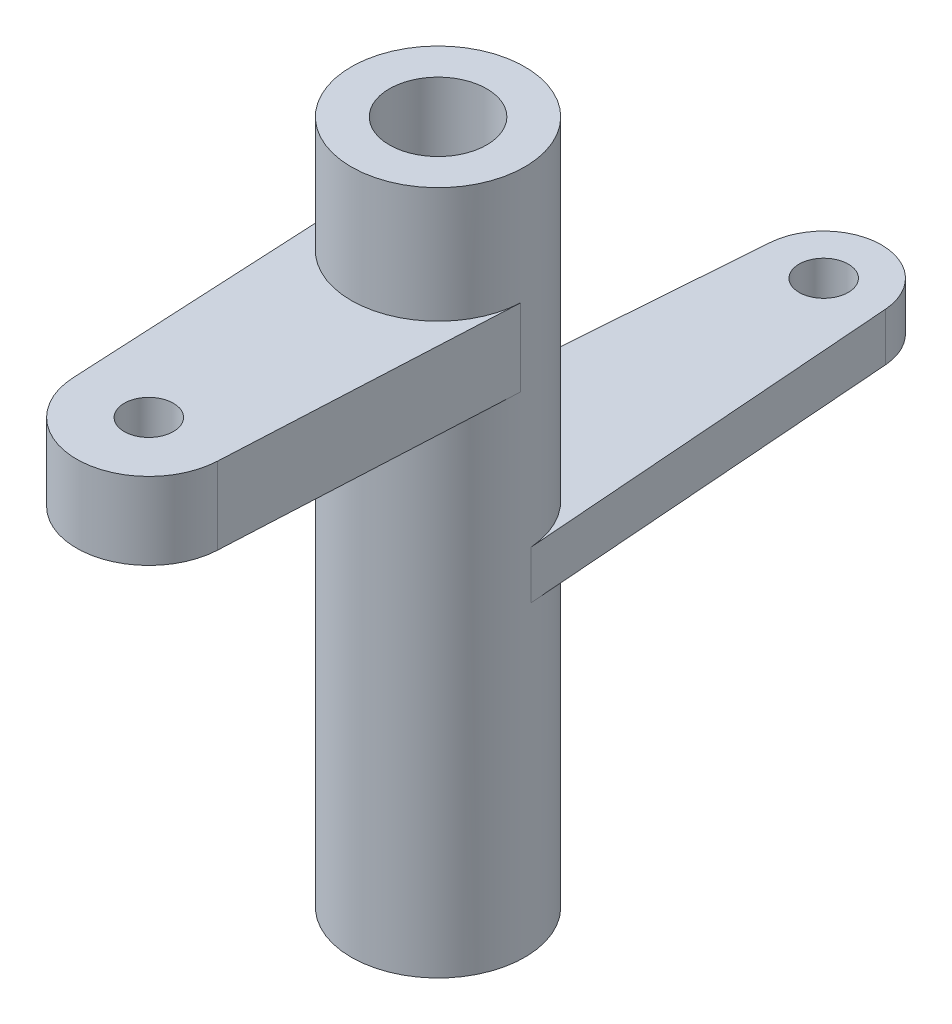
SolidWorks part; units mm, degrees
ref_plane "前视基准面" through (0, 0, 0) normal (0, 0, 1) x (1, 0, 0)
ref_plane "上视基准面" through (0, 0, 0) normal (0, 1, 0) x (1, 0, 0)
ref_plane "右视基准面" through (0, 0, 0) normal (1, 0, 0) x (0, 0, -1)
sketch "草图1" plane through (0, 0, 0) normal (0, 1, 0) x (1, 0, 0)
  circle A0 centre (0, 0) radius 5.05
  circle A1 centre (0, 0) radius 9
  dimension "D1" = 10.1
  dimension "D2" = 18
extrude "凸台-拉伸1" add sketch "草图1" along normal blind 71
ref_plane "基准面1" through (0, 34, 0) normal (0, 1, 0) x (1, 0, 0)
sketch "草图2" plane through (0, 34, 0) normal (0, 1, 0) x (1, 0, 0)
  line L0 (0, 0) -> (0, 40) construction
  line L1 (-5.9831, 40.45) -> (-8.9747, 0.675)
  line L2 (5.9831, 40.45) -> (8.9747, 0.675)
  circle A0 centre (0, 40) radius 6
  circle A1 centre (0, 0) radius 9 construction
  circle A2 centre (0, 0) radius 9
  circle A3 centre (0, 40) radius 2.55
  dimension "D2" = 12
  dimension "D3" = 18
  dimension "D4" = 5.1
  dimension "D1" = 40
extrude "凸台-拉伸2" add sketch "草图2" along normal mid plane 5
ref_plane "基准面2" through (0, 55, 0) normal (0, 1, 0) x (1, 0, 0)
sketch "草图3" plane through (0, 55, 0) normal (0, 1, 0) x (1, 0, 0)
  line L0 (0, 0) -> (0, -30) construction
  line L1 (-7.4906, -30.375) -> (-8.9887, -0.45)
  line L2 (7.4906, -30.375) -> (8.9887, -0.45)
  circle A0 centre (0, 0) radius 9
  circle A1 centre (0, -30) radius 7.5
  circle A2 centre (0, -30) radius 2.55
  dimension "D2" = 15
  dimension "D3" = 18
  dimension "D4" = 5.1
  dimension "D1" = 30
extrude "凸台-拉伸3" add sketch "草图3" along normal mid plane 8
